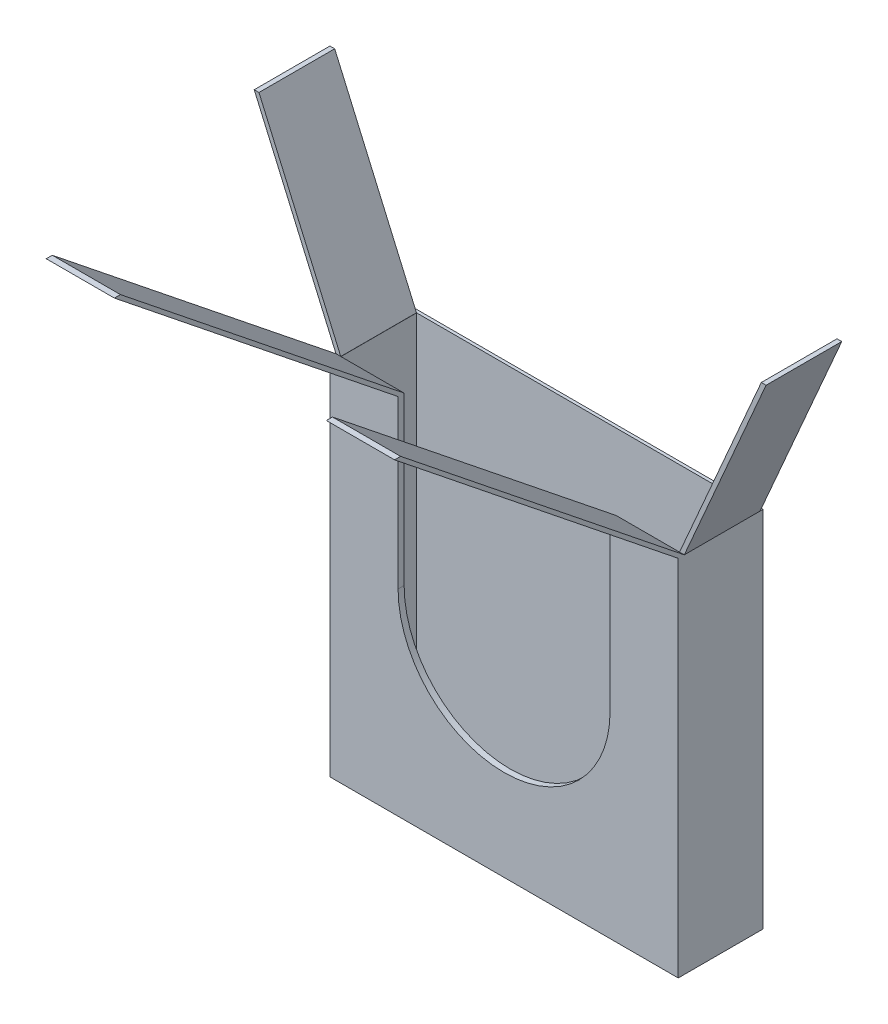
SolidWorks part; units mm, degrees
ref_plane "Front Plane" through (0, 0, 0) normal (0, 0, 1) x (1, 0, 0)
ref_plane "Top Plane" through (0, 0, 0) normal (0, 1, 0) x (1, 0, 0)
ref_plane "Right Plane" through (0, 0, 0) normal (1, 0, 0) x (0, 0, -1)
sketch "Sketch1" plane through (0, 0, 0) normal (0, 0, 1) x (1, 0, 0)
  line L0 (-88.9, 152.4) -> (-88.9, 12.7)
  line L1 (-146.05, -152.4) -> (146.05, -152.4)
  line L2 (-146.05, -152.4) -> (-146.05, 152.4)
  line L3 (-146.05, 152.4) -> (-88.9, 152.4)
  line L4 (146.05, -152.4) -> (146.05, 152.4)
  line L5 (-146.05, -152.4) -> (146.05, 152.4) construction
  line L6 (-146.05, 152.4) -> (146.05, -152.4) construction
  line L7 (88.9, 152.4) -> (88.9, 12.7)
  line L8 (88.9, 152.4) -> (146.05, 152.4)
  arc A0 (-88.9, 12.7) -> (88.9, 12.7) centre (0, 12.7) ccw
  point P0 (0, 0)
  point P6 (-88.9, 152.4)
  point P7 (88.9, 152.4)
  point P11 (0, -76.2)
  point P15 (0, -152.4)
  dimension "D1" = 292.1
  dimension "D2" = 177.8
  dimension "D4" = 76.2
  dimension "D5" = 304.8
extrude "Boss-Extrude1" add sketch "Sketch1" along normal blind 5.08
sketch "Sketch2" plane through (146.05, 0, 0) normal (1, 0, 0) x (0, 0, -1)
  line L0 (-5.08, 152.4) -> (-243.0144, 342.9)
  line L1 (-243.0144, 342.9) -> (-237.9344, 342.9)
  line L2 (-237.9344, 342.9) -> (0, 152.4)
  line L3 (-5.08, 152.4) -> (0, 152.4) construction
  line L4 (-5.08, 152.4) -> (0, 152.4)
  line L5 (0, 152.4) -> (-219.9465, 152.4) construction
  line L6 (0, 152.4) -> (0, 471.6339) construction
  dimension "D1" = 190.5
  dimension "D2" = 304.8
extrude "Boss-Extrude2" add sketch "Sketch2" against normal up to surface (57.15 mm away) up to face at (88.9, 82.55, 2.54)
sketch "Sketch3" plane through (0, 0, 0) normal (0, 0, -1) x (-1, 0, 0)
  line L0 (88.9, 152.4) -> (146.05, 152.4) construction
  line L1 (-142.0596, -147.1724) -> (141.9347, -147.1724)
  line L2 (-142.0596, -147.1724) -> (-142.0596, 152.4)
  line L3 (-142.0596, 152.4) -> (141.9347, 152.4)
  line L4 (141.9347, -147.1724) -> (141.9347, 152.4)
  line L5 (-142.0596, -147.1724) -> (141.9347, 152.4) construction
  line L6 (-142.0596, 152.4) -> (141.9347, -147.1724) construction
  line L7 (-88.9, 152.4) -> (-146.05, 152.4)
  line L8 (-146.05, 152.4) -> (-146.05, -152.4)
  line L9 (-146.05, -152.4) -> (146.05, -152.4)
  line L10 (146.05, -152.4) -> (146.05, 152.4)
  line L11 (146.05, 152.4) -> (88.9, 152.4)
  line L12 (88.9, 152.4) -> (88.9, 12.7)
  line L13 (-88.9, 12.7) -> (-88.9, 152.4)
  line L14 (-142.0596, 152.4) -> (-146.05, 152.4)
  line L15 (-146.05, 152.4) -> (-146.05, -152.4)
  line L16 (-146.05, -152.4) -> (146.05, -152.4)
  line L17 (146.05, -152.4) -> (146.05, 152.4)
  line L18 (146.05, 152.4) -> (141.9347, 152.4)
  arc A1 (-88.9, 12.7) -> (88.9, 12.7) centre (0, 12.7) ccw
  point P2 (-0.0625, 2.6138)
  line M12 (-88.9, 152.4) -> (-146.05, 152.4)
  line M13 (-146.05, 152.4) -> (-146.05, -152.4)
  line M14 (-146.05, -152.4) -> (146.05, -152.4)
  line M15 (146.05, -152.4) -> (146.05, 152.4)
  line M16 (146.05, 152.4) -> (88.9, 152.4)
  dimension "D1" = 0
extrude "Boss-Extrude3" add sketch "Sketch3" along normal blind 63.5 contours L4 L1 L2 M12 M13 M14 M15 M16
sketch "Sketch4" plane through (0, 0, -63.5) normal (0, 0, -1) x (-1, 0, 0)
  line L0 (-146.05, 152.4) -> (-214.6251, 309.8624)
  line L1 (-214.6251, 309.8624) -> (-210.6347, 309.8624)
  line L2 (-210.6347, 309.8624) -> (-142.0596, 152.4)
  line L3 (-142.0596, 152.4) -> (-146.05, 152.4)
extrude "Boss-Extrude4" add sketch "Sketch4" against normal up to surface (63.5 mm away) up to face at (0.0312, 31.4694, 0)
mirror "Mirror3" about plane through (0, 0, 0) normal (1, 0, 0) of "Boss-Extrude4"
sketch "Sketch6" plane through (-88.9, 0, 0) normal (1, 0, 0) x (0, 0, -1)
  line L0 (-5.08, 152.4) -> (-243.0144, 342.9)
  line L1 (-243.0144, 342.9) -> (-237.9344, 342.9)
  line L2 (-237.9344, 342.9) -> (0, 152.4)
  line L3 (-5.08, 152.4) -> (0, 152.4) construction
  line L4 (0, 152.4) -> (-5.08, 152.4)
  line L5 (-243.0144, 342.9) -> (-237.9344, 342.9) construction
  line L6 (-237.9344, 342.9) -> (0, 152.4) construction
extrude "Boss-Extrude5" add sketch "Sketch6" against normal up to surface (57.15 mm away) up to face at (-146.05, 30.48, -23.368)
sketch "Sketch7" plane through (0, 0, -63.5) normal (0, 0, -1) x (-1, 0, 0)
  line L1 (-146.05, -152.4) -> (146.05, -152.4)
  line L2 (-146.05, -152.4) -> (-146.05, 152.4)
  line L3 (-146.05, 152.4) -> (146.05, 152.4)
  line L4 (146.05, -152.4) -> (146.05, 152.4)
extrude "Boss-Extrude6" add sketch "Sketch7" along normal blind 2.54
